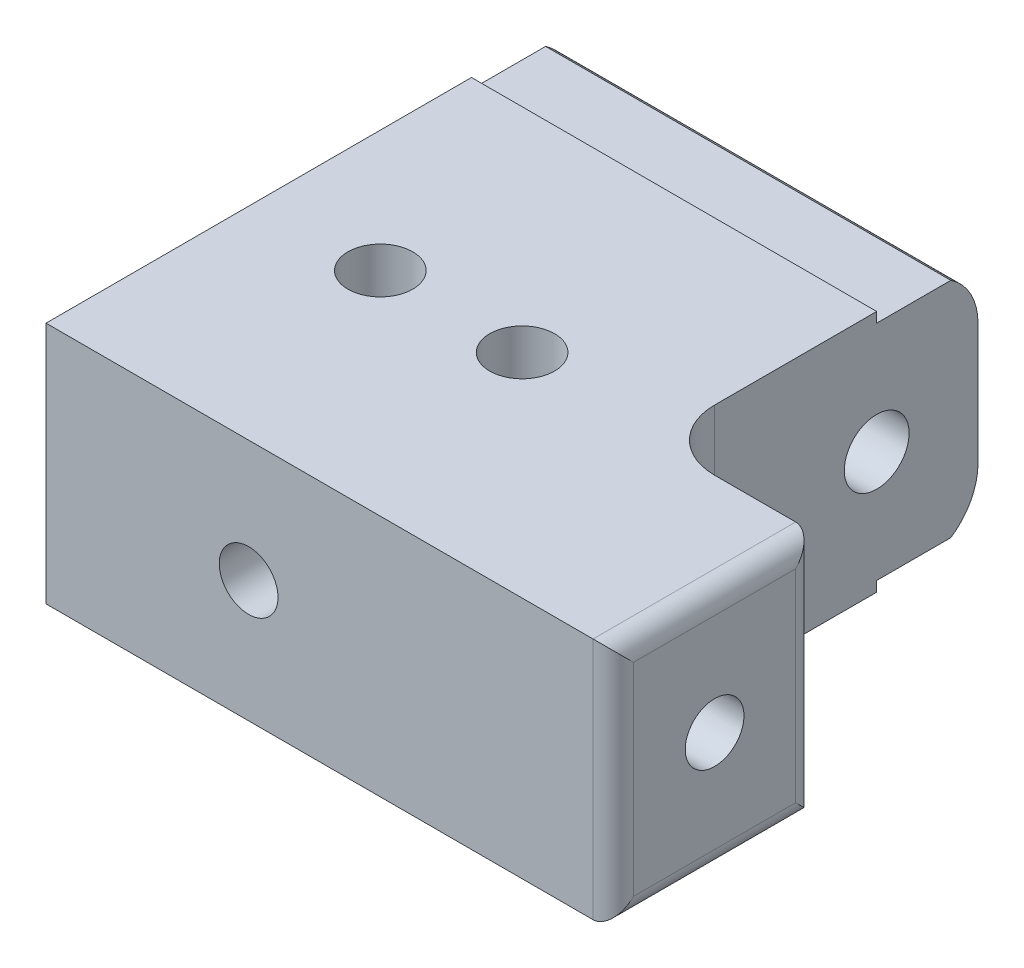
SolidWorks part; units mm, degrees
ref_plane "Front" through (0, 0, 0) normal (0, 0, 1) x (1, 0, 0)
ref_plane "Top" through (0, 0, 0) normal (0, 1, 0) x (1, 0, 0)
ref_plane "Right" through (0, 0, 0) normal (1, 0, 0) x (0, 0, -1)
sketch "Sketch1" plane through (0, 0, 0) normal (0, 0, 1) x (1, 0, 0)
  line L1 (0, 0) -> (20, 0)
  line L2 (0, 0) -> (0, -12)
  line L3 (0, -12) -> (20, -12)
  line L4 (20, 0) -> (20, -12)
  dimension "D1" = 20
  dimension "D2" = 12
extrude "Boss-Extrude1" add sketch "Sketch1" along normal blind 26
sketch "Sketch2" plane through (20, 0, 0) normal (1, 0, 0) x (0, 0, -1)
  line L0 (-26, 0) -> (0, 0) construction
  line L1 (-26, -12) -> (-16, -12)
  line L2 (-26, -12) -> (-26, 0)
  line L3 (-26, 0) -> (-16, 0)
  line L4 (-16, -12) -> (-16, 0)
  dimension "D1" = 10
extrude "Boss-Extrude2" add sketch "Sketch2" along normal blind 8
sketch "Sketch3" plane through (0, 0, 0) normal (-1, 0, 0) x (0, 0, 1)
  line L0 (0, 0) -> (0, -12) construction
  line L1 (26, 0) -> (26, -12) construction
  line L2 (26, -12) -> (0, -12) construction
  circle A0 centre (5, -6) radius 1.6
  circle A1 centre (21, -6) radius 1.45
  dimension "D1" = 3.2
  dimension "D3" = 2.9
  dimension "D2" = 5
  dimension "D4" = 5
  dimension "D5" = 6
  dimension "D6" = 6
extrude "Cut-Extrude1" cut sketch "Sketch3" against normal through all
sketch "Sketch4" plane through (0, 0, 0) normal (0, 1, 0) x (1, 0, 0)
  line L0 (28, -26) -> (0, -26) construction
  line L1 (0, -26) -> (0, 0) construction
  circle A0 centre (13, -15.5) radius 1.6
  circle A1 centre (6, -15.5) radius 1.6
  dimension "D1" = 3.2
  dimension "D2" = 3.2
  dimension "D3" = 7
  dimension "D4" = 10.5
  dimension "D5" = 6
  dimension "D6" = 10.5
extrude "Cut-Extrude2" cut sketch "Sketch4" against normal through all
fillet "Fillet1" radius 3 1 edges at (20, -6, 16)
fillet "Fillet2" radius 1 4 edges at (28, 0, 21) (28, -6, 16) (28, -12, 21) (28, -6, 26)
fillet "Fillet3" radius 3 2 edges at (10, -12, 0) (10, 0, 0)
sketch "Sketch5" plane through (0, 0, 0) normal (-1, 0, 0) x (0, 0, 1)
  line L0 (26, -12) -> (3, -12) construction
  line L1 (5, -12) -> (-4.9767, -12)
  line L2 (5, -12) -> (5, -11.5)
  line L3 (5, -11.5) -> (-4.9767, -11.5)
  line L4 (-4.9767, -12) -> (-4.9767, -11.5)
  line L5 (26, 0) -> (3, 0) construction
  line L6 (5, 0) -> (-7.2599, 0)
  line L7 (5, 0) -> (5, -0.5)
  line L8 (5, -0.5) -> (-7.2599, -0.5)
  line L9 (-7.2599, 0) -> (-7.2599, -0.5)
  line L10 (0, -3) -> (0, -9) construction
  dimension "D1" = 0.5
  dimension "D2" = 0.5
  dimension "D3" = 5
  dimension "D4" = 5
extrude "Cut-Extrude3" cut sketch "Sketch5" against normal through all
sketch "Sketch6" plane through (0, 0, 0) normal (0, 0, -1) x (-1, 0, 0)
  line L1 (-12.75, 7.3758) -> (-7.25, 7.3758)
  line L2 (-12.75, 7.3758) -> (-12.75, -23.1123)
  line L3 (-12.75, -23.1123) -> (-7.25, -23.1123)
  line L4 (-7.25, 7.3758) -> (-7.25, -23.1123)
  dimension "D1" = 5.5
  dimension "D2" = 7.25
extrude "Cut-Extrude4" cut sketch "Sketch6" against normal blind 0.8
sketch "Sketch7" plane through (0, 0, 26) normal (0, 0, 1) x (1, 0, 0)
  line L0 (0, 0) -> (0, -12) construction
  circle A0 centre (10, -6) radius 1.45
  dimension "D1" = 2.9
  dimension "D2" = 10
extrude "Cut-Extrude5" cut sketch "Sketch7" against normal blind 8
